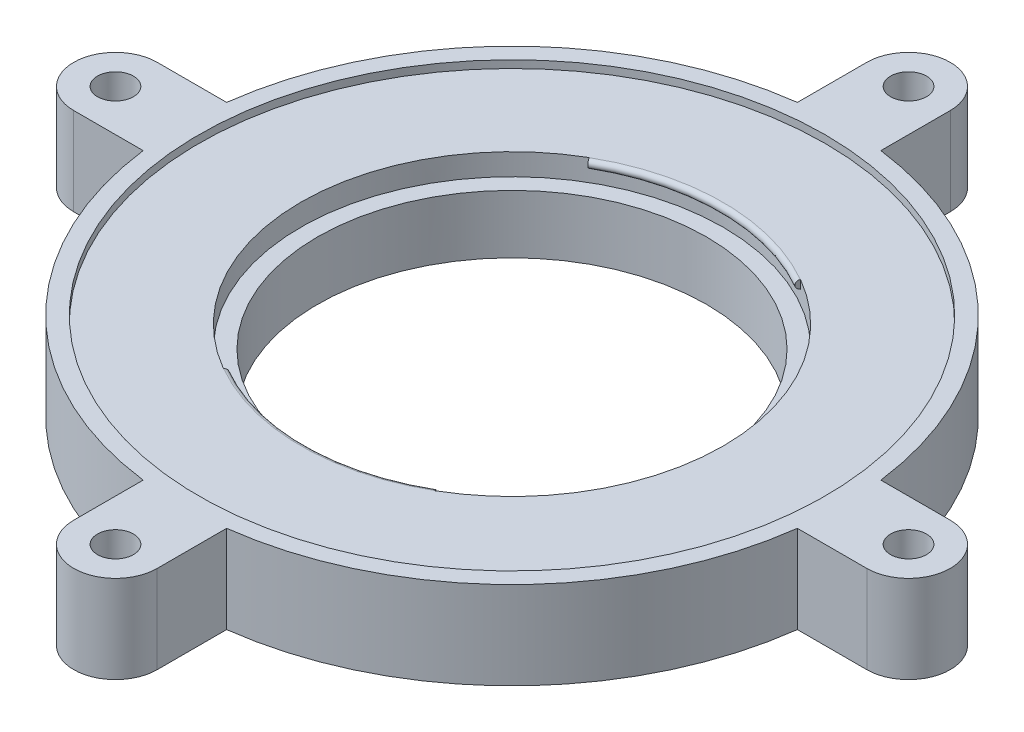
SolidWorks part; units mm, degrees
ref_plane "Front Plane" through (0, 0, 0) normal (0, 0, 1) x (1, 0, 0)
ref_plane "Top Plane" through (0, 0, 0) normal (0, 1, 0) x (1, 0, 0)
ref_plane "Right Plane" through (0, 0, 0) normal (1, 0, 0) x (0, 0, -1)
sketch "Sketch1" plane through (0, 0, 0) normal (1, 0, 0) x (0, 0, -1)
  line L0 (-37.5, -1.0482) -> (-37.5, -1.9554)
  line L1 (-37.5, -1.9554) -> (-25.283, -1.9554)
  line L2 (-25.3, -3.0472) -> (-25.3, -4.5554)
  line L3 (-25.3, -4.5554) -> (-8, -4.5554)
  line L4 (-8, -4.5554) -> (-8, -11.5554)
  line L5 (-8, -11.5554) -> (-39.5, -11.5554)
  line L6 (-39.5, -11.5554) -> (-39.5, -1.0482)
  line L9 (-39.5, -1.0482) -> (-37.5, -1.0482)
  line L10 (0, -1000) -> (0, 49000) construction
  arc A0 (-25.283, -1.9554) -> (-25.2165, -2.9486) centre (-25.299, -2.4553) cw
  arc A1 (-25.2165, -2.9486) -> (-25.3, -3.0472) centre (-25.2, -3.0472) ccw
  point P13 (-24.8, -2.4219)
  point P15 (-25.3, -2.9554)
  point P17 (-37.5, -1.5018)
  dimension "D2" = 1.6
  dimension "D4" = 1
  dimension "D9" = 0.1
  dimension "D1" = 25.3
  dimension "D3" = 0.5
  dimension "D5" = 37.5
  dimension "D6" = 7
  dimension "D7" = 2
  dimension "D8" = 8
revolve "Revolve1" add sketch "Sketch1" angle 360 about L10
sketch "Sketch2" plane through (0, -11.5554, 0) normal (0, -1, 0) x (1, 0, 0)
  line L0 (0, 0) -> (0, 47.5) construction
  line L1 (-5, 47.5) -> (-5, 39.1823)
  line L2 (5, 47.5) -> (5, 39.1823)
  line L3 (5, 39.1823) -> (-5, 39.1823)
  line L4 (47.5, -5) -> (39.1823, -5)
  line L5 (47.5, 5) -> (39.1823, 5)
  line L6 (39.1823, -5) -> (39.1823, 5)
  line L7 (-5, -47.5) -> (-5, -39.1823)
  line L8 (5, -47.5) -> (5, -39.1823)
  line L9 (-5, -39.1823) -> (5, -39.1823)
  line L10 (-47.5, 5) -> (-39.1823, 5)
  line L11 (-47.5, -5) -> (-39.1823, -5)
  line L12 (-39.1823, 5) -> (-39.1823, -5)
  circle A0 centre (0, 47.5) radius 2.15
  arc A1 (5, 47.5) -> (-5, 47.5) centre (0, 47.5) ccw
  circle A2 centre (0, 0) radius 39.5 construction
  arc A3 (47.5, -5) -> (47.5, 5) centre (47.5, 0) ccw
  arc A4 (-5, -47.5) -> (5, -47.5) centre (0, -47.5) ccw
  arc A5 (-47.5, 5) -> (-47.5, -5) centre (-47.5, 0) ccw
  circle A6 centre (47.5, 0) radius 2.15
  circle A7 centre (0, -47.5) radius 2.15
  circle A8 centre (-47.5, 0) radius 2.15
  point P28 (0, 0)
  dimension "D2" = 4.3
  dimension "D3" = 10
  dimension "D1" = 47.5
  dimension "D4" = 4
extrude "Boss-Extrude1" add sketch "Sketch2" against normal up to surface (10.5072 mm away) up to face at (0, -1.0482, -37.5)
sketch "Sketch3" plane through (0, -4.5554, 0) normal (0, 1, 0) x (1, 0, 0)
  line L0 (0, 0) -> (50000, 0) construction
  line L1 (21.9383, -2) -> (12.3693, -2)
  line L2 (2, -12.3693) -> (2, -21.9383)
  line L3 (0, -0.3712) -> (0, -50000.3712) construction
  line L4 (-2, -21.9383) -> (-2, -12.3693)
  line L5 (-12.3693, -2) -> (-21.9383, -2)
  line L6 (-21.9383, 2) -> (-12.3693, 2)
  line L7 (-2, 12.3693) -> (-2, 21.9383)
  line L8 (2, 21.9383) -> (2, 12.3693)
  line L9 (12.3693, 2) -> (21.9383, 2)
  arc A1 (3.3846, -10.4663) -> (10.4663, -3.3846) centre (0, 0) ccw
  circle A2 centre (0, 0) radius 8 construction
  arc A4 (4.3587, -23.9059) -> (23.9059, -4.3587) centre (0, 0) ccw
  arc A5 (2, -12.3693) -> (3.3846, -10.4663) centre (4, -12.3693) cw
  arc A6 (2, -21.9383) -> (4.3587, -23.9059) centre (4, -21.9383) ccw
  arc A7 (21.9383, -2) -> (23.9059, -4.3587) centre (21.9383, -4) cw
  arc A8 (12.3693, -2) -> (10.4663, -3.3846) centre (12.3693, -4) ccw
  arc A9 (-23.9059, -4.3587) -> (-4.3587, -23.9059) centre (0, 0) ccw
  arc A10 (-2, -21.9383) -> (-4.3587, -23.9059) centre (-4, -21.9383) cw
  arc A11 (-2, -12.3693) -> (-3.3846, -10.4663) centre (-4, -12.3693) ccw
  arc A12 (-10.4663, -3.3846) -> (-3.3846, -10.4663) centre (0, 0) ccw
  arc A13 (-12.3693, -2) -> (-10.4663, -3.3846) centre (-12.3693, -4) cw
  arc A14 (-21.9383, -2) -> (-23.9059, -4.3587) centre (-21.9383, -4) ccw
  arc A15 (-4.3587, 23.9059) -> (-23.9059, 4.3587) centre (0, 0) ccw
  arc A16 (-21.9383, 2) -> (-23.9059, 4.3587) centre (-21.9383, 4) cw
  arc A17 (-12.3693, 2) -> (-10.4663, 3.3846) centre (-12.3693, 4) ccw
  arc A18 (-3.3846, 10.4663) -> (-10.4663, 3.3846) centre (0, 0) ccw
  arc A19 (-2, 12.3693) -> (-3.3846, 10.4663) centre (-4, 12.3693) cw
  arc A20 (-2, 21.9383) -> (-4.3587, 23.9059) centre (-4, 21.9383) ccw
  arc A21 (23.9059, 4.3587) -> (4.3587, 23.9059) centre (0, 0) ccw
  arc A22 (2, 21.9383) -> (4.3587, 23.9059) centre (4, 21.9383) cw
  arc A23 (2, 12.3693) -> (3.3846, 10.4663) centre (4, 12.3693) ccw
  arc A24 (10.4663, 3.3846) -> (3.3846, 10.4663) centre (0, 0) ccw
  arc A25 (12.3693, 2) -> (10.4663, 3.3846) centre (12.3693, 4) cw
  arc A26 (21.9383, 2) -> (23.9059, 4.3587) centre (21.9383, 4) ccw
  point P59 (0, 0)
  dimension "D2" = 2
  dimension "D3" = 2
  dimension "D4" = 2
  dimension "D5" = 4
extrude "Cut-Extrude2" cut sketch "Sketch3" against normal up to surface (7 mm away)
sketch "Sketch4" plane through (0, -11.5554, 0) normal (0, -1, 0) x (-1, 0, 0)
  line L0 (0, 0) -> (30, 0) construction
  line L1 (0, 0) -> (50000, 0) construction
  circle A0 centre (30, 0) radius 2.15
  circle A1 centre (0, -30) radius 2.15
  circle A2 centre (-30, 0) radius 2.15
  circle A3 centre (0, 30) radius 2.15
  point P15 (0, 0)
  dimension "D3" = 4.3
  dimension "D1" = 0
  dimension "D2" = 30
  dimension "D4" = 4
extrude "Cut-Extrude3" cut sketch "Sketch4" against normal blind 7
sketch "Sketch5" plane through (0, -11.5554, 0) normal (0, -1, 0) x (1, 0, 0)
  circle A0 centre (0, 0) radius 23.3
  circle A1 centre (0, 0) radius 24.3
  arc A2 (-4.3587, 23.9059) -> (-23.9059, 4.3587) centre (0, 0) ccw construction
  dimension "D1" = 1
extrude "Boss-Extrude2" add sketch "Sketch5" against normal up to surface (7 mm away) up to face at (10.4854, -4.5554, -10.4854)
sketch "Sketch6" plane through (0, -4.5554, 0) normal (0, 1, 0) x (1, 0, 0)
  circle A0 centre (0, 0) radius 23.3
extrude "Cut-Extrude4" cut sketch "Sketch6" against normal through all
sketch "Sketch7" plane through (0, -4.5554, 0) normal (0, 1, 0) x (1, 0, 0)
  line L0 (0, 0) -> (12.65, -21.9104)
  line L1 (0, 0) -> (-12.65, -21.9104)
  line L2 (0, 0) -> (0, -25.3) construction
  line L3 (-1000, 0) -> (49000, 0) construction
  line L4 (0, 0) -> (12.65, 21.9104)
  line L5 (0, 0) -> (-12.65, 21.9104)
  circle A0 centre (0, 0) radius 25.3 construction
  arc A1 (12.65, -21.9104) -> (12.65, 21.9104) centre (0, 0) ccw
  arc A2 (-12.65, -21.9104) -> (-12.65, 21.9104) centre (0, 0) cw
  circle M6 centre (0, 0) radius 23.3
  circle M7 centre (0, 0) radius 25.3
  dimension "D1" = 30
  dimension "D2" = 30
extrude "Cut-Extrude5" cut sketch "Sketch7" along normal through all contours L4 L0 M6 | L1 L5 M6 | L4 L0 M6 M7 | L5 L1 M6 M7
equation "\"D4@Sketch3\"=\"D3@Sketch3\""
equation "\"D2@Sketch7\"=\"D1@Sketch7\""
